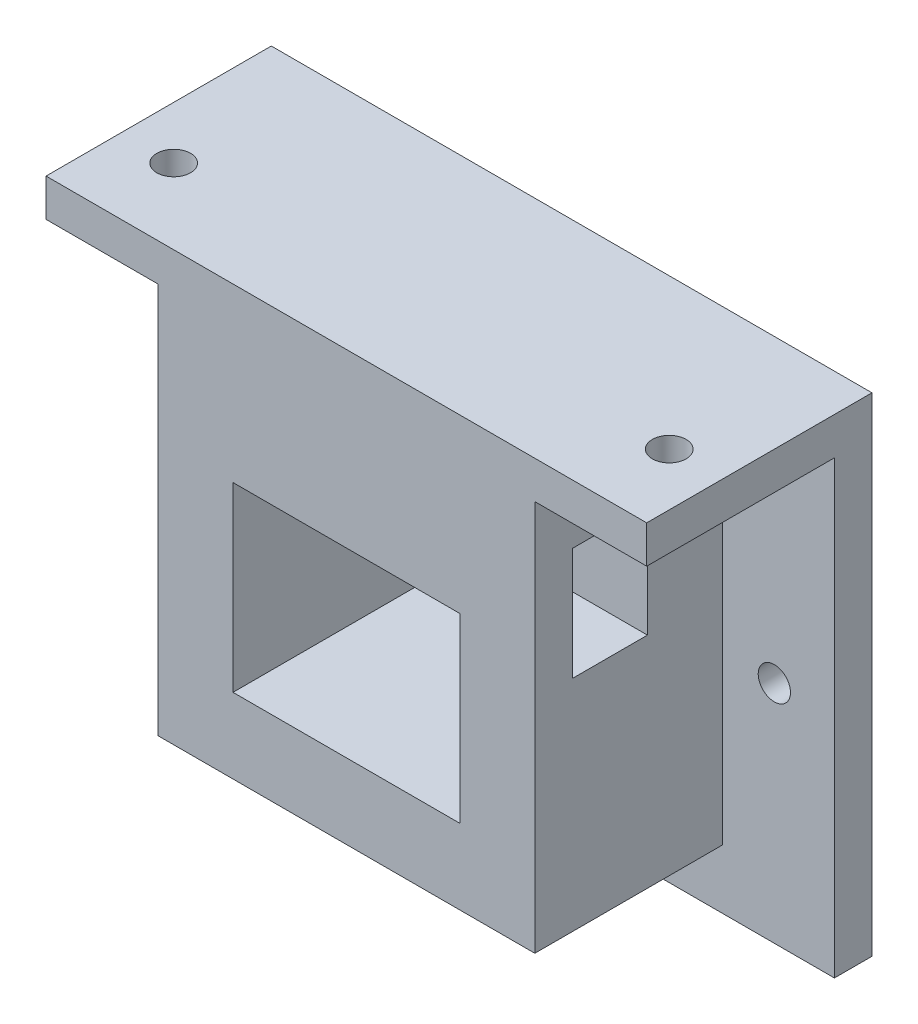
SolidWorks part; units mm, degrees
ref_plane "Front Plane" through (0, 0, 0) normal (0, 0, 1) x (1, 0, 0)
ref_plane "Top Plane" through (0, 0, 0) normal (0, 1, 0) x (1, 0, 0)
ref_plane "Right Plane" through (0, 0, 0) normal (1, 0, 0) x (0, 0, -1)
sketch "Sketch1" plane through (0, 0, 0) normal (0, 0, 1) x (1, 0, 0)
  line L1 (0, 0) -> (80, 0)
  line L2 (0, 0) -> (0, 60)
  line L3 (0, 60) -> (80, 60)
  line L4 (80, 0) -> (80, 60)
  dimension "D1" = 80
  dimension "D2" = 60
extrude "Boss-Extrude1" add sketch "Sketch1" along normal blind 5
sketch "Sketch2" plane through (0, 0, 5) normal (0, 0, 1) x (1, 0, 0)
  line L0 (24.9, 42.1) -> (55.1, 17.9) construction
  line L1 (24.9, 17.9) -> (55.1, 17.9)
  line L2 (24.9, 17.9) -> (24.9, 42.1)
  line L3 (24.9, 42.1) -> (55.1, 42.1)
  line L4 (55.1, 17.9) -> (55.1, 42.1)
  line L5 (24.9, 17.9) -> (55.1, 42.1) construction
  line L6 (0, 0) -> (80, 0) construction
  line L7 (80, 0) -> (80, 60) construction
  line L8 (14.9, 52.1) -> (65.1, 52.1)
  line L9 (65.1, 7.9) -> (65.1, 52.1)
  line L10 (14.9, 7.9) -> (65.1, 7.9)
  line L11 (14.9, 7.9) -> (14.9, 52.1)
  point P4 (40, 30)
  point P8 (40, 0)
  point P12 (80, 30)
  dimension "D1" = 30.2
  dimension "D2" = 24.2
  dimension "D3" = 10
extrude "Boss-Extrude2" add sketch "Sketch2" along normal blind 25
sketch "Sketch3" plane through (55.1, 0, 0) normal (-1, 0, 0) x (0, 0, 1)
  line L1 (15, 37.1) -> (25, 37.1)
  line L2 (15, 37.1) -> (15, 52.1)
  line L3 (15, 52.1) -> (25, 52.1)
  line L4 (25, 37.1) -> (25, 52.1)
  line L7 (30, 52.1) -> (5, 52.1) construction
  line L8 (30, 42.1) -> (5, 42.1) construction
  line L9 (5, 60) -> (5, 0) construction
  dimension "D1" = 10
  dimension "D2" = 10
  dimension "D3" = 0
  dimension "D4" = 5
extrude "Cut-Extrude1" cut sketch "Sketch3" along normal through all both and the other way through all
sketch "Sketch4" plane through (0, 0, 5) normal (0, 0, 1) x (1, 0, 0)
  line L0 (80, 60) -> (0, 60) construction
  line L1 (14.9, 52.1) -> (65.1, 52.1)
  line L2 (14.9, 52.1) -> (14.9, 60)
  line L3 (14.9, 60) -> (65.1, 60)
  line L4 (65.1, 52.1) -> (65.1, 60)
extrude "Boss-Extrude3" add sketch "Sketch4" along normal up to surface (25 mm away) up to face at (40, 30, 30)
chamfer "Chamfer1" distance 7.7 angle 45 1 edges at (40, 42.1, 5)
sketch "Sketch5" plane through (0, 60, 0) normal (0, 1, 0) x (1, 0, 0)
  line L1 (14.9, -5) -> (0, -5)
  line L2 (14.9, -5) -> (14.9, -30)
  line L3 (14.9, -30) -> (0, -30)
  line L4 (0, -5) -> (0, -30)
  line L5 (65.1, -30) -> (80, -30)
  line L6 (65.1, -30) -> (65.1, -5)
  line L7 (65.1, -5) -> (80, -5)
  line L8 (80, -30) -> (80, -5)
  line L12 (80, 0) -> (0, 0)
  line L13 (0, 0) -> (0, -5)
  line L14 (0, -5) -> (14.9, -5)
  line L15 (14.9, -5) -> (14.9, -30)
  line L16 (14.9, -30) -> (65.1, -30)
  line L17 (65.1, -30) -> (65.1, -5)
  line L18 (65.1, -5) -> (80, -5)
  line L19 (80, -5) -> (80, 0)
  line L20 (80, 0) -> (0, 0)
  line L21 (0, 0) -> (0, -5)
  line L22 (0, -5) -> (14.9, -5)
  line L23 (14.9, -5) -> (14.9, -30)
  line L24 (14.9, -30) -> (65.1, -30)
  line L25 (65.1, -30) -> (65.1, -5)
  line L26 (65.1, -5) -> (80, -5)
  line L27 (80, -5) -> (80, 0)
  line M13 (80, 0) -> (0, 0)
  line M14 (0, 0) -> (0, -5)
  line M15 (0, -5) -> (14.9, -5)
  line M16 (14.9, -5) -> (14.9, -30)
  line M17 (14.9, -30) -> (65.1, -30)
  line M18 (65.1, -30) -> (65.1, -5)
  line M19 (65.1, -5) -> (80, -5)
  line M20 (80, -5) -> (80, 0)
  dimension "D1" = 0
extrude "Boss-Extrude4" add sketch "Sketch5" along normal blind 5 contours L4 L3 M15 M16 | M20 M13 M14 M15 M16 M17 M18 M19 | L5 L8 M19 M18
sketch "Sketch6" plane through (0, 60, 0) normal (0, -1, 0) x (1, 0, 0)
  line L0 (14.9, 25) -> (14.9, 15) construction
  line L1 (14.9, 25) -> (14.9, 15)
  line L2 (14.9, 30) -> (65.1, 30) construction
  circle A0 centre (7, 20) radius 2.25
  point P4 (14.9, 20)
  point P5 (40, 20)
  point P8 (40, 30)
  dimension "D1" = 4.5
  dimension "D2" = 33
extrude "Cut-Extrude3" cut sketch "Sketch6" against normal up to surface (5 mm away) contours A0
ref_plane "Plane1" through (40, 0, 0) normal (-1, 0, 0) x (0, 0, 1)
mirror "Mirror1" about plane through (40, 0, 0) normal (-1, 0, 0) of "Cut-Extrude3"
sketch "Sketch7" plane through (0, 0, 5) normal (0, 0, 1) x (1, 0, 0)
  line L0 (0, 30) -> (80, 30) construction
  line L1 (0, 60) -> (0, 0) construction
  line L2 (80, 0) -> (80, 60) construction
  line L3 (40, 13.75) -> (40, -13.75) construction
  circle A0 centre (8, 30) radius 2.15
  circle A1 centre (72, 30) radius 2.15
  dimension "D1" = 4.3
  dimension "D2" = 8
extrude "Cut-Extrude4" cut sketch "Sketch7" against normal through all both and the other way through all
